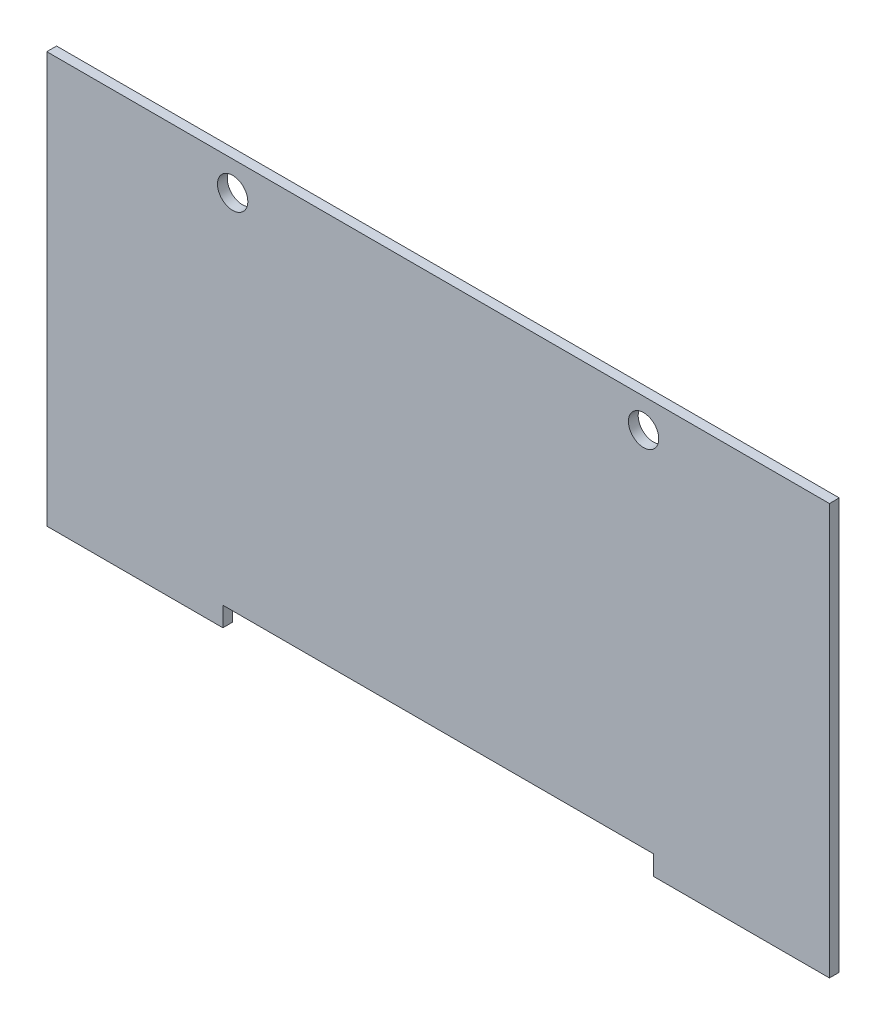
SolidWorks part; units mm, degrees
ref_plane "前视基准面" through (0, 0, 0) normal (0, 0, 1) x (1, 0, 0)
ref_plane "上视基准面" through (0, 0, 0) normal (0, 1, 0) x (1, 0, 0)
ref_plane "右视基准面" through (0, 0, 0) normal (1, 0, 0) x (0, 0, -1)
sketch "草图1" plane through (0, 0, 0) normal (0, 0, 1) x (1, 0, 0)
  line L0 (0, 0) -> (0, 42)
  line L1 (0, 42) -> (80, 42)
  line L2 (80, 42) -> (80, 0)
  line L3 (80, 0) -> (62, 0)
  line L4 (62, 0) -> (62, 2)
  line L5 (62, 2) -> (18, 2)
  line L6 (18, 2) -> (18, 0)
  line L7 (18, 0) -> (0, 0)
  line L8 (19, 39) -> (61, 39) construction
  line L9 (40, 42) -> (40, 39) construction
  circle A0 centre (19, 39) radius 1.55
  circle A1 centre (61, 39) radius 1.55
  dimension "D7" = 3.1
  dimension "D1" = 42
  dimension "D2" = 40
  dimension "D3" = 44
  dimension "D4" = 80
  dimension "D5" = 3
  dimension "D6" = 42
extrude "凸台-拉伸1" add sketch "草图1" along normal blind 1
